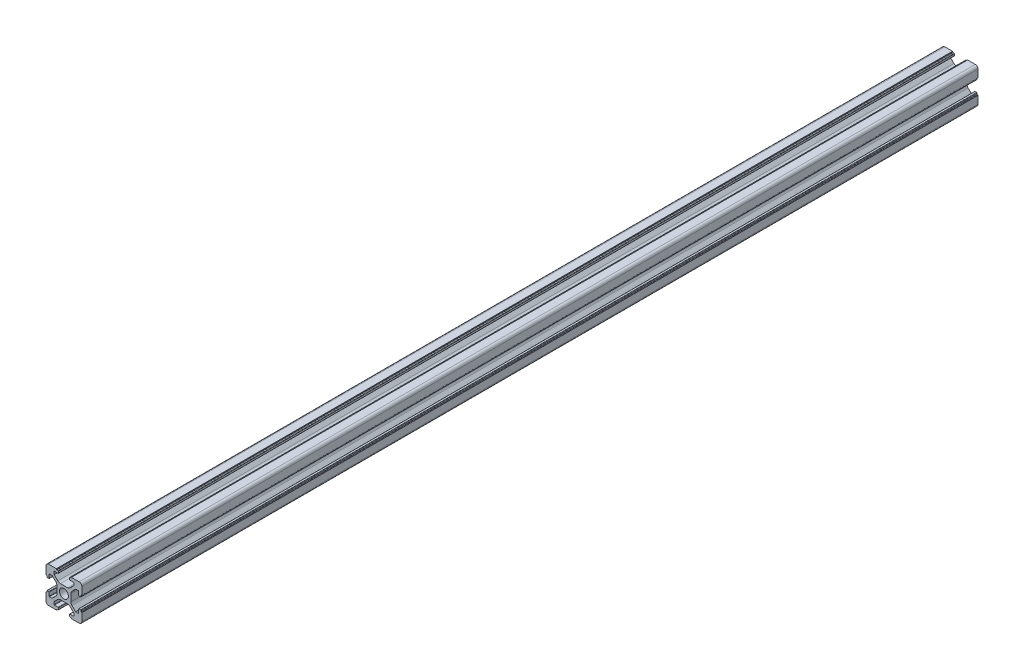
SolidWorks part; units mm, degrees
material "6063-T5"
ref_plane "Front Plane" through (0, 0, 0) normal (0, 0, 1) x (1, 0, 0)
ref_plane "Top Plane" through (0, 0, 0) normal (0, 1, 0) x (1, 0, 0)
ref_plane "Right Plane" through (0, 0, 0) normal (1, 0, 0) x (0, 0, -1)
sketch "Sketch1" plane through (0, 0, 0) normal (0, 0, -1) x (1, 0, 0)
  line L0 (1.5, 0) -> (5.8, 0)
  line L1 (20, 1.5) -> (20, 5.8)
  line L2 (18.5, 20) -> (14.2, 20)
  line L3 (0, 18.5) -> (0, 14.2)
  line L4 (14.2, 0) -> (18.5, 0)
  line L5 (13.3, 18.2) -> (15.3, 18.2)
  line L6 (20, 14.2) -> (20, 18.5)
  line L7 (0, 5.8) -> (0, 1.5)
  line L8 (6.7, 18.2) -> (4.7, 18.2)
  line L9 (1.8, 13.3) -> (1.8, 15.3)
  line L10 (19.3, 13.1) -> (18.4, 13.1)
  line L11 (19.3, 6.9) -> (18.4, 6.9)
  line L12 (6.9, 19.3) -> (6.9, 18.4)
  line L13 (13.1, 19.3) -> (13.1, 18.4)
  line L14 (0.7, 13.1) -> (1.6, 13.1)
  line L15 (0.7, 6.9) -> (1.6, 6.9)
  line L16 (13.4251, 14.4858) -> (15.4121, 16.4728)
  line L17 (14.4858, 13.4251) -> (16.4728, 15.4121)
  line L18 (14.4858, 6.5749) -> (16.4728, 4.5879)
  line L19 (13.4251, 5.5142) -> (15.4121, 3.5272)
  line L20 (6.5749, 5.5142) -> (4.5879, 3.5272)
  line L21 (5.5142, 6.5749) -> (3.5272, 4.5879)
  line L22 (5.5142, 13.4251) -> (3.5272, 15.4121)
  line L23 (6.5749, 14.4858) -> (4.5879, 16.4728)
  line L24 (6.9, 0.7) -> (6.9, 1.6)
  line L25 (13.1, 0.7) -> (13.1, 1.6)
  line L26 (5.8, 20) -> (1.5, 20)
  line L27 (1.8, 6.7) -> (1.8, 4.7)
  line L28 (6.7, 1.8) -> (4.7, 1.8)
  line L29 (13.3, 1.8) -> (15.3, 1.8)
  line L30 (18.2, 13.3) -> (18.2, 15.3)
  line L31 (18.2, 6.7) -> (18.2, 4.7)
  line L32 (2, 4.5) -> (3.3151, 4.5)
  line L33 (2, 15.5) -> (3.3151, 15.5)
  line L34 (4.5, 18) -> (4.5, 16.6849)
  line L35 (15.5, 18) -> (15.5, 16.6849)
  line L36 (18, 15.5) -> (16.6849, 15.5)
  line L37 (4.5, 2) -> (4.5, 3.3151)
  line L38 (15.5, 2) -> (15.5, 3.3151)
  line L39 (18, 4.5) -> (16.6849, 4.5)
  line L40 (7.9891, 13.9) -> (12.0109, 13.9)
  line L41 (7.9891, 6.1) -> (12.0109, 6.1)
  line L42 (13.9, 12.0109) -> (13.9, 7.9891)
  line L43 (6.1, 12.0109) -> (6.1, 7.9891)
  line L44 (19.5, 6.7) -> (19.5, 6.1)
  line L45 (5.9, 19.9) -> (5.9, 19.7)
  line L46 (6.1, 19.5) -> (6.7, 19.5)
  line L47 (14.1, 19.9) -> (14.1, 19.7)
  line L48 (13.9, 19.5) -> (13.3, 19.5)
  line L49 (0.1, 14.1) -> (0.3, 14.1)
  line L50 (0.5, 13.9) -> (0.5, 13.3)
  line L51 (0.1, 5.9) -> (0.3, 5.9)
  line L52 (0.5, 6.1) -> (0.5, 6.7)
  line L53 (19.9, 14.1) -> (19.7, 14.1)
  line L54 (19.5, 13.9) -> (19.5, 13.3)
  line L55 (19.7, 5.9) -> (19.9, 5.9)
  line L56 (14.1, 0.1) -> (14.1, 0.3)
  line L57 (13.9, 0.5) -> (13.3, 0.5)
  line L58 (6.7, 0.5) -> (6.1, 0.5)
  line L59 (5.9, 0.3) -> (5.9, 0.1)
  circle A0 centre (10, 10) radius 2.5
  arc A1 (18.5, 0) -> (20, 1.5) centre (18.5, 1.5) ccw
  arc A2 (1.5, 0) -> (0, 1.5) centre (1.5, 1.5) cw
  arc A3 (20, 18.5) -> (18.5, 20) centre (18.5, 18.5) ccw
  arc A4 (1.5, 20) -> (0, 18.5) centre (1.5, 18.5) ccw
  arc A5 (12.0109, 6.1) -> (13.4251, 5.5142) centre (12.0109, 4.1) cw
  arc A6 (13.9, 7.9891) -> (14.4858, 6.5749) centre (15.9, 7.9891) ccw
  arc A7 (13.9, 12.0109) -> (14.4858, 13.4251) centre (15.9, 12.0109) cw
  arc A8 (12.0109, 13.9) -> (13.4251, 14.4858) centre (12.0109, 15.9) ccw
  arc A9 (7.9891, 13.9) -> (6.5749, 14.4858) centre (7.9891, 15.9) cw
  arc A10 (6.1, 7.9891) -> (5.5142, 6.5749) centre (4.1, 7.9891) cw
  arc A11 (6.1, 12.0109) -> (5.5142, 13.4251) centre (4.1, 12.0109) ccw
  arc A12 (13.1, 1.6) -> (13.3, 1.8) centre (13.3, 1.6) cw
  arc A13 (6.9, 1.6) -> (6.7, 1.8) centre (6.7, 1.6) ccw
  arc A14 (6.1, 0.5) -> (5.9, 0.3) centre (6.1, 0.3) ccw
  arc A15 (6.7, 0.5) -> (6.9, 0.7) centre (6.7, 0.7) ccw
  arc A16 (1.6, 6.9) -> (1.8, 6.7) centre (1.6, 6.7) cw
  arc A17 (0.5, 6.7) -> (0.7, 6.9) centre (0.7, 6.7) cw
  arc A18 (0.5, 13.3) -> (0.7, 13.1) centre (0.7, 13.3) ccw
  arc A19 (1.6, 13.1) -> (1.8, 13.3) centre (1.6, 13.3) ccw
  arc A20 (6.7, 19.5) -> (6.9, 19.3) centre (6.7, 19.3) cw
  arc A21 (6.9, 18.4) -> (6.7, 18.2) centre (6.7, 18.4) cw
  arc A22 (13.1, 18.4) -> (13.3, 18.2) centre (13.3, 18.4) ccw
  arc A23 (13.3, 19.5) -> (13.1, 19.3) centre (13.3, 19.3) ccw
  arc A24 (18.4, 13.1) -> (18.2, 13.3) centre (18.4, 13.3) cw
  arc A25 (19.5, 13.3) -> (19.3, 13.1) centre (19.3, 13.3) cw
  arc A26 (19.5, 6.7) -> (19.3, 6.9) centre (19.3, 6.7) ccw
  arc A27 (14.1, 0.3) -> (13.9, 0.5) centre (13.9, 0.3) ccw
  arc A28 (19.5, 6.1) -> (19.7, 5.9) centre (19.7, 6.1) ccw
  arc A29 (5.9, 19.7) -> (6.1, 19.5) centre (6.1, 19.7) ccw
  arc A30 (14.1, 19.7) -> (13.9, 19.5) centre (13.9, 19.7) cw
  arc A31 (19.7, 14.1) -> (19.5, 13.9) centre (19.7, 13.9) ccw
  arc A32 (13.3, 0.5) -> (13.1, 0.7) centre (13.3, 0.7) cw
  arc A33 (0.3, 14.1) -> (0.5, 13.9) centre (0.3, 13.9) cw
  arc A34 (0.3, 5.9) -> (0.5, 6.1) centre (0.3, 6.1) ccw
  arc A35 (0, 5.8) -> (0.1, 5.9) centre (0.1, 5.8) cw
  arc A36 (5.9, 0.1) -> (5.8, 0) centre (5.8, 0.1) cw
  arc A37 (14.1, 0.1) -> (14.2, 0) centre (14.2, 0.1) ccw
  arc A38 (19.9, 5.9) -> (20, 5.8) centre (19.9, 5.8) cw
  arc A39 (20, 14.2) -> (19.9, 14.1) centre (19.9, 14.2) cw
  arc A40 (14.2, 20) -> (14.1, 19.9) centre (14.2, 19.9) ccw
  arc A41 (5.8, 20) -> (5.9, 19.9) centre (5.8, 19.9) cw
  arc A42 (0, 14.2) -> (0.1, 14.1) centre (0.1, 14.2) ccw
  arc A43 (18.4, 6.9) -> (18.2, 6.7) centre (18.4, 6.7) ccw
  arc A44 (1.8, 15.3) -> (2, 15.5) centre (2, 15.3) cw
  arc A45 (1.8, 4.7) -> (2, 4.5) centre (2, 4.7) ccw
  arc A46 (4.7, 1.8) -> (4.5, 2) centre (4.7, 2) cw
  arc A47 (15.3, 1.8) -> (15.5, 2) centre (15.3, 2) ccw
  arc A48 (18.2, 4.7) -> (18, 4.5) centre (18, 4.7) cw
  arc A49 (18.2, 15.3) -> (18, 15.5) centre (18, 15.3) ccw
  arc A50 (15.3, 18.2) -> (15.5, 18) centre (15.3, 18) cw
  arc A51 (4.7, 18.2) -> (4.5, 18) centre (4.7, 18) ccw
  arc A52 (7.9891, 6.1) -> (6.5749, 5.5142) centre (7.9891, 4.1) ccw
  arc A53 (3.3151, 15.5) -> (3.5272, 15.4121) centre (3.3151, 15.2) cw
  arc A54 (4.5, 16.6849) -> (4.5879, 16.4728) centre (4.8, 16.6849) ccw
  arc A55 (15.5, 16.6849) -> (15.4121, 16.4728) centre (15.2, 16.6849) cw
  arc A56 (16.6849, 15.5) -> (16.4728, 15.4121) centre (16.6849, 15.2) ccw
  arc A57 (16.6849, 4.5) -> (16.4728, 4.5879) centre (16.6849, 4.8) cw
  arc A58 (15.5, 3.3151) -> (15.4121, 3.5272) centre (15.2, 3.3151) ccw
  arc A59 (4.5, 3.3151) -> (4.5879, 3.5272) centre (4.8, 3.3151) cw
  arc A60 (3.3151, 4.5) -> (3.5272, 4.5879) centre (3.3151, 4.8) ccw
  point P67 (0, 0)
  point P125 (14.1, 19.5)
extrude "Boss-Extrude1" add sketch "Sketch1" along normal blind 500 contours L23 A54 L34 A51 L8 A21 L12 A20 L46 A29 L45 A41 L26 A4 L3 A42 L49 A33 L50 A18 L14 A19 L9 A44 L33 A53 L22 A11 L43 A10 L21 A60 L32 A45 L27 A16 L15 A17 L52 A34 L51 A35 L7 A2 L0 A36 L59 A14 L58 A15 L24 A13 L28 A46 L37 A59 L20 A52 L41 A5 L19 A58 L38 A47 L29 A12 L25 A32 L57 A27 L56 A37 L4 A1 L1 A38 L55 A28 L44 A26 L11 A43 L31 A48 L39 A57 L18 A6 L42 A7 L17 A56 L36 A49 L30 A24 L10 A25 L54 A31 L53 A39 L6 A3 L2 A40 L47 A30 L48 A23 L13 A22 L5 A50 L35 A55 L16 A8 L40 A9 | A0
ref_plane "topMidPlane" through (0, -10, 0) normal (0, -1, 0) x (-1, 0, 0)
ref_plane "Plane2" through (10, 0, 0) normal (-1, 0, 0) x (0, 0, 1)
